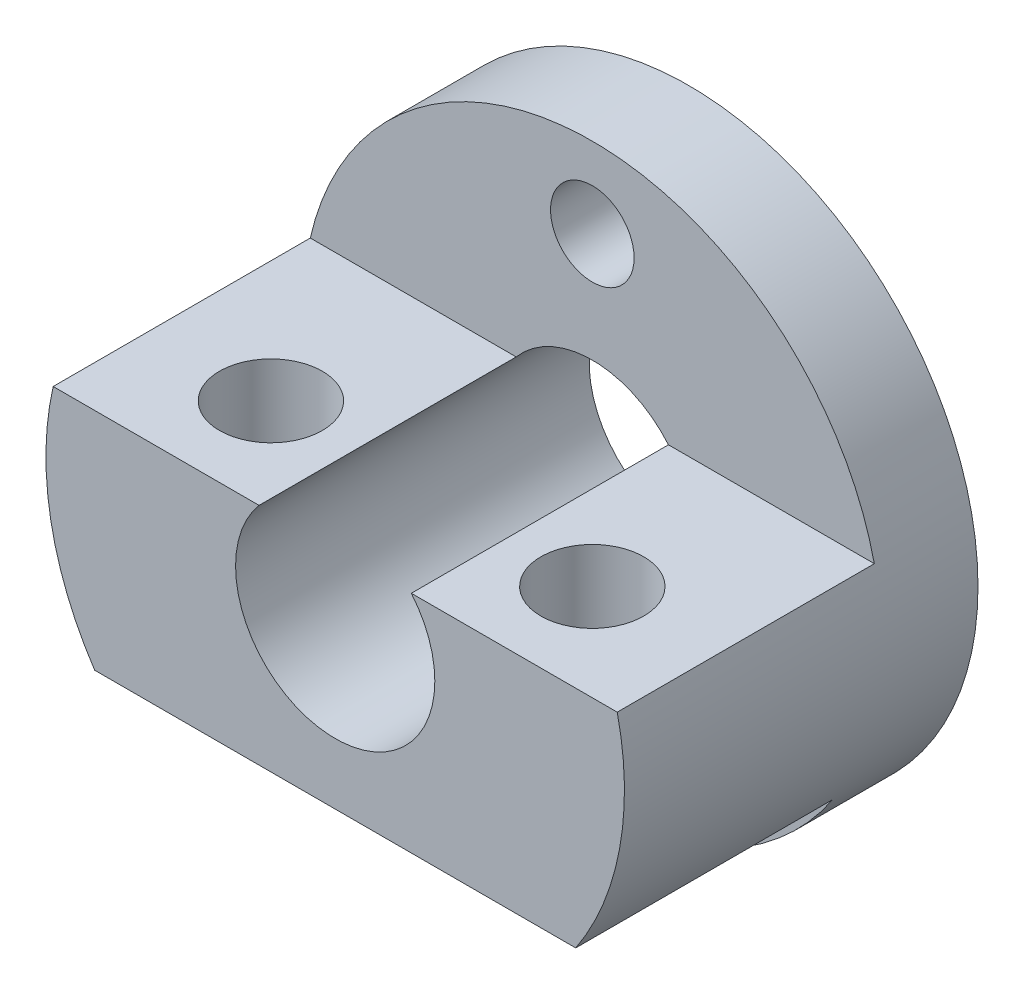
SolidWorks part; units mm, degrees
material "6061-T6 (SS)"
ref_plane "前视基准面" through (0, 0, 0) normal (0, 0, 1) x (1, 0, 0)
ref_plane "上视基准面" through (0, 0, 0) normal (0, 1, 0) x (1, 0, 0)
ref_plane "右视基准面" through (0, 0, 0) normal (1, 0, 0) x (0, 0, -1)
sketch "草图1" plane through (0, 0, 0) normal (0, 0, 1) x (1, 0, 0)
  circle A0 centre (0, 0) radius 9.5
  dimension "D1" = 19
extrude "凸台-拉伸1" add sketch "草图1" along normal blind 3
sketch "草图3" plane through (0, 0, 3) normal (0, 0, 1) x (1, 0, 0)
  circle A0 centre (0, 0) radius 9
  dimension "D1" = 18
extrude "凸台-拉伸2" add sketch "草图3" along normal blind 13
sketch "草图4" plane through (0, 0, 16) normal (0, 0, 1) x (1, 0, 0)
  line L0 (-8.775, 2) -> (8.775, 2)
  line L1 (-7.4833, -5) -> (7.4833, -5)
  circle A0 centre (0, 0) radius 9 construction
  circle A1 centre (0, 0) radius 9 construction
  arc A2 (-8.775, 2) -> (8.775, 2) centre (0, 0) cw
  arc A3 (7.4833, -5) -> (-7.4833, -5) centre (0, 0) cw
  dimension "D1" = 2
  dimension "D2" = 5
extrude "切除-拉伸2" cut sketch "草图4" against normal blind 13
sketch "草图5" plane through (0, 0, 16) normal (0, 0, 1) x (1, 0, 0)
  circle A0 centre (0, 0) radius 3.1
  dimension "D1" = 6.2
extrude "切除-拉伸3" cut sketch "草图5" against normal blind 20
sketch "草图6" plane through (0, 2, 0) normal (0, 1, 0) x (1, 0, 0)
  line L0 (2.3685, -3) -> (8.775, -3) construction
  line L1 (-8.775, -3) -> (-2.3685, -3) construction
  line L2 (-3.1, -16) -> (3.1, -16) construction
  circle A0 centre (-5, -8) radius 1.6
  circle A1 centre (5, -8) radius 1.6
  circle A2 centre (0, -14) radius 1.6
  dimension "D1" = 5
  dimension "D2" = 5
  dimension "D3" = 10
  dimension "D4" = 5
  dimension "D5" = 3.2
  dimension "D6" = 3.2
  dimension "D7" = 2
  dimension "D8" = 3.2
extrude "切除-拉伸4" cut sketch "草图6" against normal blind 20
sketch "草图7" plane through (0, 0, 3) normal (0, 0, 1) x (1, 0, 0)
  circle A0 centre (0, 6.5) radius 1.3
  circle A1 centre (0, -6.5) radius 1.3
  dimension "D1" = 6.5
  dimension "D2" = 2.6
  dimension "D3" = 2.6
  dimension "D4" = 6.5
extrude "切除-拉伸5" cut sketch "草图7" against normal blind 20
sketch "草图8" plane through (0, 0, 16) normal (0, 0, 1) x (1, 0, 0)
  circle A0 centre (0, 0) radius 9
extrude "切除-拉伸6" cut sketch "草图8" against normal blind 5
sketch "草图9" plane through (0, 0, 3) normal (0, 0, 1) x (1, 0, 0)
  circle A0 centre (0, 0) radius 9
extrude "切除-拉伸7" cut sketch "草图9" against normal blind 13 flip side to cut
